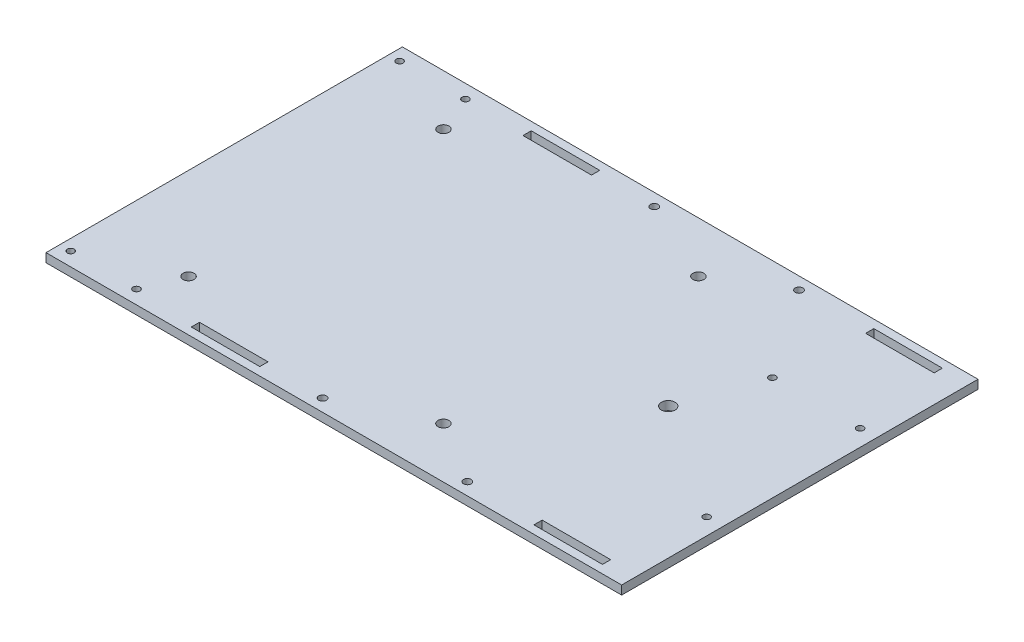
SolidWorks part; units mm, degrees
ref_plane "Front Plane" through (0, 0, 0) normal (0, 0, 1) x (1, 0, 0)
ref_plane "Top Plane" through (0, 0, 0) normal (0, 1, 0) x (1, 0, 0)
ref_plane "Right Plane" through (0, 0, 0) normal (1, 0, 0) x (0, 0, -1)
sketch "Sketch2" plane through (0, 0, 0) normal (0, 1, 0) x (1, 0, 0)
  line L1 (-50, -50) -> (50, -50) construction
  line L2 (-50, -50) -> (-50, 50) construction
  line L3 (-50, 50) -> (50, 50) construction
  line L4 (50, -50) -> (50, 50) construction
  line L5 (-50, -50) -> (50, 50) construction
  line L6 (-50, 50) -> (50, -50) construction
  line L11 (-80, 65) -> (130, 65)
  line L12 (-80, 65) -> (-80, -65)
  line L13 (-80, -65) -> (130, -65)
  line L14 (130, 65) -> (130, -65)
  line L15 (87, -33) -> (129, -33) construction
  line L16 (87, -33) -> (87, 33) construction
  line L17 (87, 33) -> (129, 33) construction
  line L18 (129, -33) -> (129, 33) construction
  line L19 (87, -33) -> (129, 33) construction
  line L20 (87, 33) -> (129, -33) construction
  circle A0 centre (-46.5, 46.5) radius 2
  circle A1 centre (46.5, 46.5) radius 2
  circle A2 centre (-46.5, -46.5) radius 2
  circle A3 centre (46.5, -46.5) radius 2
  circle A4 centre (92, 28) radius 1.25
  circle A5 centre (124, 28) radius 1.25
  circle A6 centre (124, -28) radius 1.25
  point P0 (0, 0)
  point P14 (0, 0)
  point P19 (-80, 0)
  point P20 (108, 0)
  dimension "D3" = 4
  dimension "D14" = 2.5
  dimension "D1" = 100
  dimension "D2" = 100
  dimension "D4" = 3.5
  dimension "D5" = 3.5
  dimension "D6" = 3.5
  dimension "D7" = 3.5
  dimension "D8" = 15
  dimension "D9" = 30
  dimension "D10" = 210
  dimension "D11" = 58
  dimension "D12" = 42
  dimension "D13" = 66
  dimension "D15" = 5
  dimension "D16" = 5
  dimension "D17" = 5
  dimension "D18" = 5
extrude "main" add sketch "Sketch2" along normal blind 3.2
sketch "Sketch3" plane through (0, 3.2, 0) normal (0, 1, 0) x (1, 0, 0)
  line L0 (-80, 0) -> (130, 0) construction
  line L1 (-80, -65) -> (-48, -65) construction
  line L2 (-80, -65) -> (-80, -55) construction
  line L3 (-80, -55) -> (-48, -55) construction
  line L4 (-48, -65) -> (-48, -55) construction
  line L5 (-80, 65) -> (-80, -65) construction
  line L6 (130, -65) -> (130, 65) construction
  circle A0 centre (-76, -60) radius 1.25
  circle A1 centre (-52, -60) radius 1.25
  circle A2 centre (-52, 60) radius 1.25
  circle A3 centre (-76, 60) radius 1.25
  point P16 (-80, -60)
  dimension "D3" = 2.5
  dimension "D1" = 32
  dimension "D2" = 10
  dimension "D4" = 4
  dimension "D5" = 4
extrude "motor mount" cut sketch "Sketch3" against normal up to surface (3.2 mm away) up to face at (25, 0, 0)
sketch "Sketch4" plane through (0, 3.2, 0) normal (0, 1, 0) x (1, 0, 0)
  line L0 (-80, -65) -> (130, -65) construction
  line L1 (-30, -59) -> (-5, -59)
  line L2 (-30, -59) -> (-30, -62)
  line L3 (-30, -62) -> (-5, -62)
  line L4 (-5, -59) -> (-5, -62)
  line L5 (-80, 65) -> (-80, -65) construction
  line L6 (95, -59) -> (120, -59)
  line L7 (95, -59) -> (95, -62)
  line L8 (95, -62) -> (120, -62)
  line L9 (120, -59) -> (120, -62)
  line L10 (-80, 0) -> (130, 0) construction
  line L11 (130, -65) -> (130, 65) construction
  line L12 (95, 62) -> (120, 62)
  line L13 (95, 59) -> (120, 59)
  line L14 (120, 59) -> (120, 62)
  line L15 (95, 59) -> (95, 62)
  line L16 (-5, 59) -> (-5, 62)
  line L17 (-30, 62) -> (-5, 62)
  line L18 (-30, 59) -> (-30, 62)
  line L19 (-30, 59) -> (-5, 59)
  circle A0 centre (16.4, -60.5) radius 1.4
  circle A1 centre (69.2, -60.5) radius 1.4
  circle A2 centre (69.2, 60.5) radius 1.4
  circle A3 centre (16.4, 60.5) radius 1.4
  point P29 (-5, -60.5)
  dimension "D7" = 2.8
  dimension "D1" = 3
  dimension "D2" = 3
  dimension "D3" = 25
  dimension "D4" = 50
  dimension "D6" = 100
  dimension "D8" = 21.4
  dimension "D9" = 52.8
  dimension "D5" = 2
extrude "side holes" cut sketch "Sketch4" against normal up to surface (3.2 mm away) up to face at (-76, 0, -58.75)
sketch "Sketch5" plane through (0, 3.2, 0) normal (0, 1, 0) x (1, 0, 0)
  circle A2 centre (82, 0) radius 2.5
  point P2 (0, 0)
  dimension "D1" = 5
  dimension "D2" = 82
extrude "back wheel" cut sketch "Sketch5" against normal up to surface (3.2 mm away) up to face at (107.5, 0, 60.5)
equation "\"D6@Sketch2\"=\"D4@Sketch2\""
equation "\"D7@Sketch2\"=\"D5@Sketch2\""
equation "\"D5@Sketch3\"=\"D4@Sketch3\""
equation "\"D17@Sketch2\"=\"D16@Sketch2\""
equation "\"D18@Sketch2\"=\"D16@Sketch2\""
equation "\"D15@Sketch2\"=\"D16@Sketch2\""
